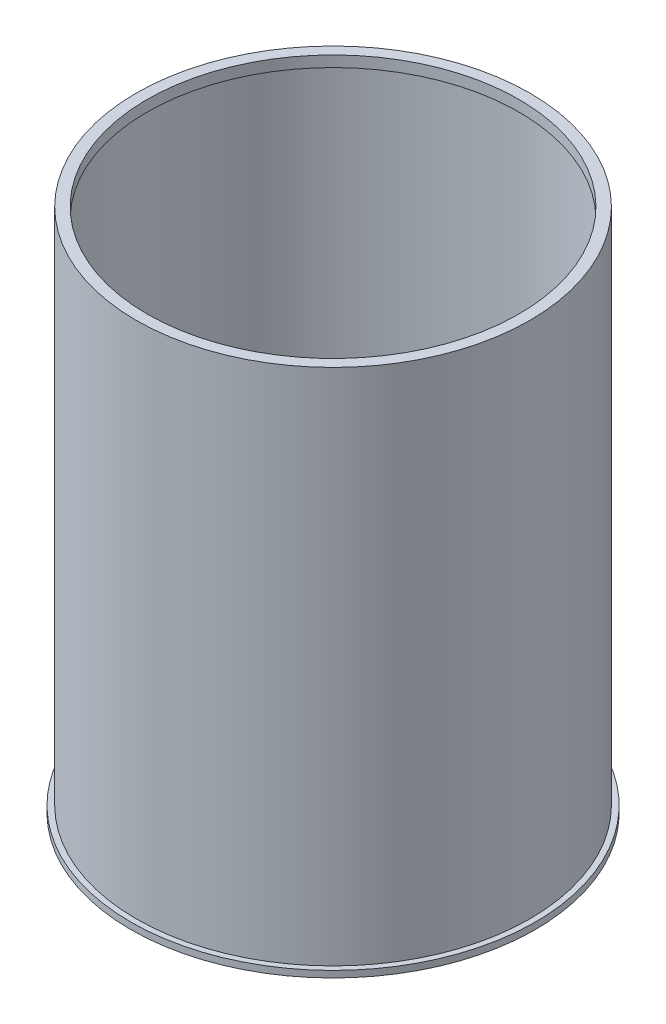
SolidWorks part; units mm, degrees
material "PE High Density"
ref_plane "Front Plane" through (0, 0, 0) normal (0, 0, 1) x (1, 0, 0)
ref_plane "Top Plane" through (0, 0, 0) normal (0, 1, 0) x (1, 0, 0)
ref_plane "Right Plane" through (0, 0, 0) normal (1, 0, 0) x (0, 0, -1)
sketch "Receptacle Floor Sketch" plane through (0, 0, 0) normal (0, 1, 0) x (1, 0, 0)
  circle A0 centre (0, 0) radius 185
  circle A1 centre (0, 0) radius 12.5
  dimension "D1" = 370
  dimension "D2" = 25
extrude "Receptacle Floor" add sketch "Receptacle Floor Sketch" along normal blind 6
sketch "Receptacle Wall Sketch" plane through (0, 0, 0) normal (0, 1, 0) x (1, 0, 0)
  circle A0 centre (0, 0) radius 180
  circle A1 centre (0, 0) radius 176
  dimension "D1" = 360
  dimension "D2" = 352
extrude "Receptacle Wall" add sketch "Receptacle Wall Sketch" along normal blind 480
sketch "Pot Seat Ledge Sketch" plane through (0, 0, 0) normal (0, 1, 0) x (1, 0, 0)
  circle A0 centre (0, 0) radius 177
  circle A1 centre (0, 0) radius 170
  dimension "D1" = 354
  dimension "D2" = 340
extrude "Pot Seat Ledge" add sketch "Pot Seat Ledge Sketch" along normal blind 10 from offset 470
